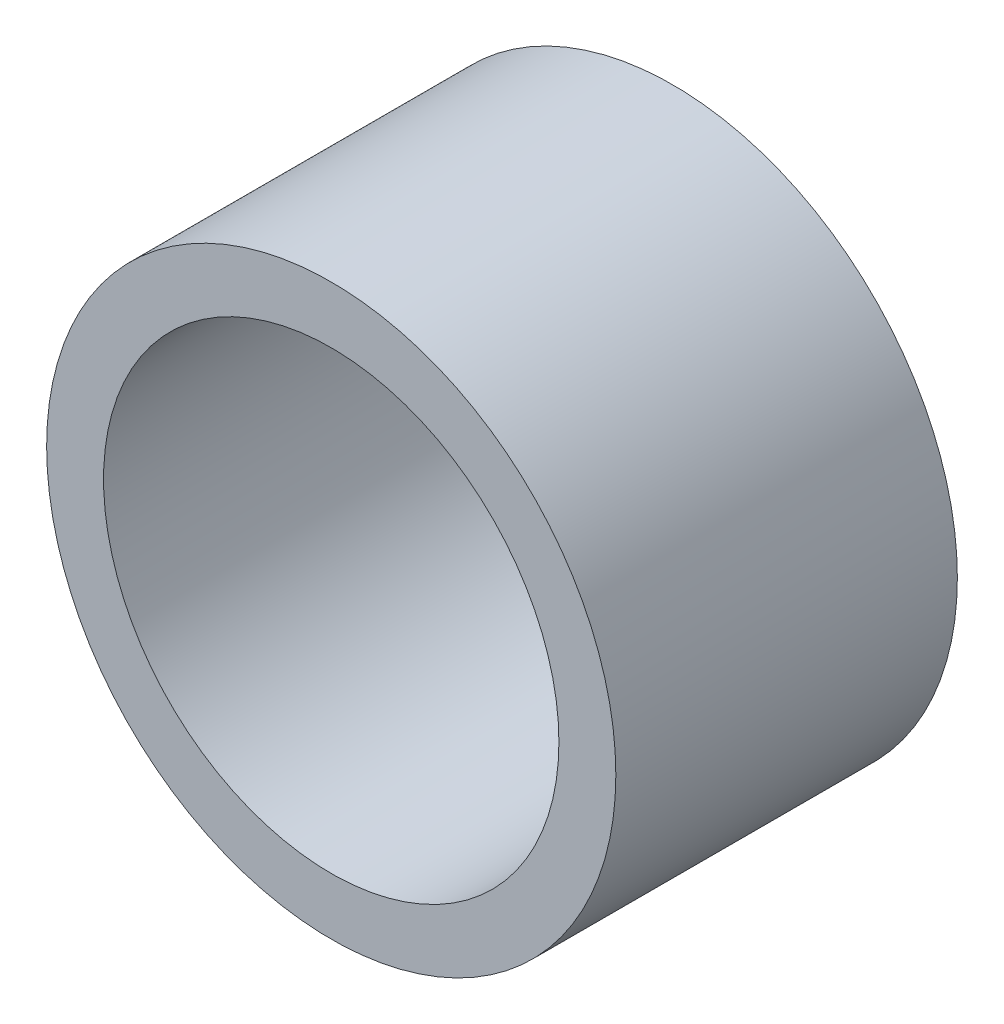
SolidWorks part; units mm, degrees
material "Thornel Mat VMA"
ref_plane "前视基准面" through (0, 0, 0) normal (0, 0, 1) x (1, 0, 0)
ref_plane "上视基准面" through (0, 0, 0) normal (0, 1, 0) x (1, 0, 0)
ref_plane "右视基准面" through (0, 0, 0) normal (1, 0, 0) x (0, 0, -1)
sketch "草图1" plane through (0, 0, 0) normal (0, 0, 1) x (1, 0, 0)
  circle A0 centre (0, 0) radius 5
  circle A1 centre (0, 0) radius 4
  dimension "D1" = 10
  dimension "D2" = 8
extrude "凸台-拉伸1" add sketch "草图1" along normal blind 6
